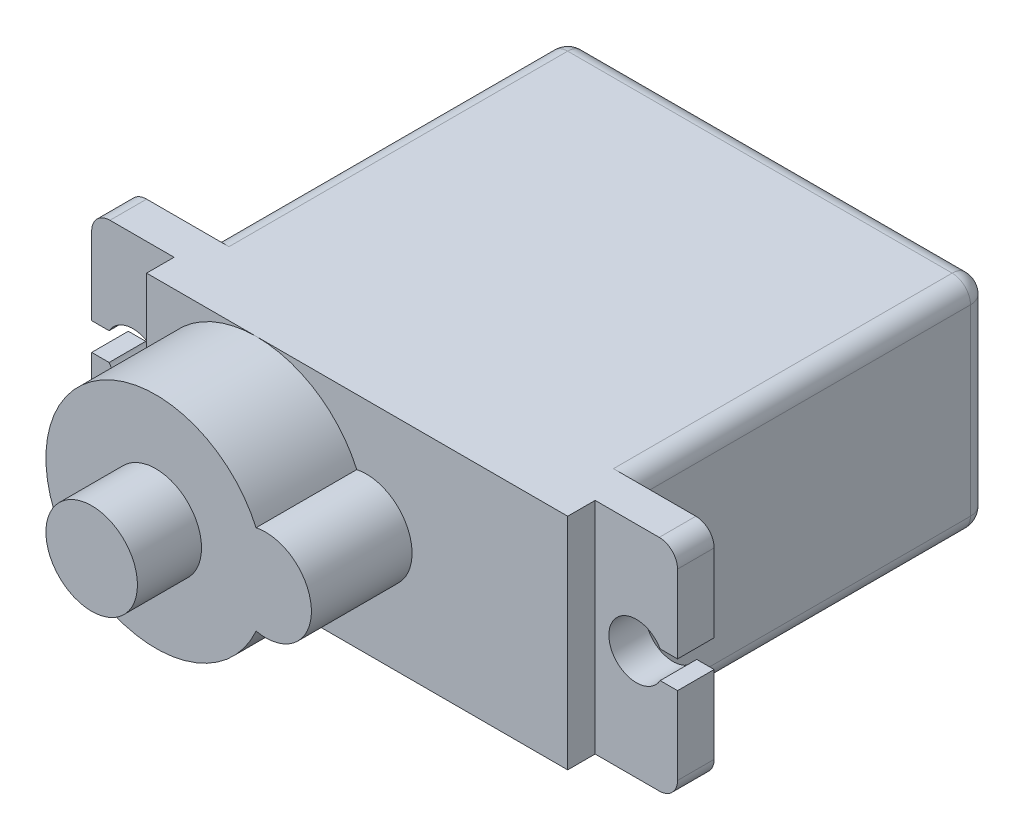
SolidWorks part; units mm, degrees
ref_plane "Front Plane" through (0, 0, 0) normal (0, 0, 1) x (1, 0, 0)
ref_plane "Top Plane" through (0, 0, 0) normal (0, 1, 0) x (1, 0, 0)
ref_plane "Right Plane" through (0, 0, 0) normal (1, 0, 0) x (0, 0, -1)
sketch "Sketch1" plane through (0, 0, 0) normal (0, 0, 1) x (1, 0, 0)
  line L1 (0, 12) -> (23, 12)
  line L2 (0, 12) -> (0, 0)
  line L3 (0, 0) -> (23, 0)
  line L4 (23, 12) -> (23, 0)
  dimension "D1" = 23
  dimension "D2" = 12
extrude "Boss-Extrude1" add sketch "Sketch1" along normal blind 32
sketch "Sketch2" plane through (0, 0, 0) normal (0, -1, 0) x (1, 0, 0)
  line L0 (0, 32) -> (0, 0) construction
  line L1 (-4.5, 21.5) -> (0, 21.5)
  line L2 (-4.5, 21.5) -> (-4.5, 19.5)
  line L3 (-4.5, 19.5) -> (0, 19.5)
  line L4 (0, 21.5) -> (0, 19.5)
  line L5 (23, 32) -> (23, 0) construction
  line L6 (23, 21.5) -> (27.5, 21.5)
  line L7 (23, 21.5) -> (23, 19.5)
  line L8 (23, 19.5) -> (27.5, 19.5)
  line L9 (27.5, 21.5) -> (27.5, 19.5)
  dimension "D1" = 4.5
  dimension "D2" = 2
  dimension "D3" = 19.5
extrude "Boss-Extrude2" add sketch "Sketch2" against normal up to surface (12 mm away) up to face at (11.5, 12, 16)
sketch "Sketch3" plane through (0, 0, 21.5) normal (0, 0, 1) x (1, 0, 0)
  line L0 (-3.549, 6.75) -> (-4.5, 6.75)
  line L1 (-3.549, 5.25) -> (-4.5, 5.25)
  line L2 (26.549, 6.75) -> (27.5, 6.75)
  line L3 (26.549, 5.25) -> (27.5, 5.25)
  line L4 (27.5, 12) -> (27.5, 0) construction
  line L5 (27.5, 6.75) -> (27.5, 5.25)
  line L6 (-4.5, 12) -> (-4.5, 0) construction
  line L7 (-4.5, 6.75) -> (-4.5, 5.25)
  arc A0 (-3.549, 5.25) -> (-3.549, 6.75) centre (-2.25, 6) ccw
  arc A1 (26.549, 6.75) -> (26.549, 5.25) centre (25.25, 6) ccw
  dimension "D4" = 3
  dimension "D1" = 6
  dimension "D2" = 2.25
  dimension "D3" = 2.25
  dimension "D5" = 0.75
  dimension "D6" = 0.75
  dimension "D7" = 0.75
  dimension "D8" = 0.75
extrude "Cut-Extrude1" cut sketch "Sketch3" against normal through all
sketch "Sketch4" plane through (0, 0, 32) normal (0, 0, 1) x (1, 0, 0)
  line L1 (0, 0) -> (23, 0)
  line L2 (0, 0) -> (0, 12)
  line L3 (0, 12) -> (23, 12)
  line L4 (23, 0) -> (23, 12)
  circle A0 centre (6, 6) radius 2.5
  dimension "D3" = 5
  dimension "D1" = 6
  dimension "D2" = 6
extrude "Cut-Extrude2" cut sketch "Sketch4" against normal blind 3.5
sketch "Sketch5" plane through (0, 0, 28.5) normal (0, 0, 1) x (1, 0, 0)
  line L1 (0, 0) -> (23, 0)
  line L2 (0, 0) -> (0, 12)
  line L3 (0, 12) -> (23, 12)
  line L4 (23, 0) -> (23, 12)
  arc A0 (11.4792, 8.4451) -> (11.4792, 3.5549) centre (6, 6) ccw
  arc A1 (11.4792, 3.5549) -> (11.4792, 8.4451) centre (12, 6) ccw
  line M4 (0, 12) -> (0, 0)
  line M5 (0, 0) -> (23, 0)
  line M6 (23, 0) -> (23, 12)
  line M7 (23, 12) -> (0, 12)
  dimension "D1" = 5
  dimension "D2" = 6
extrude "Cut-Extrude3" cut sketch "Sketch5" against normal blind 5.5 contours A1 A0 L1 M6 M7 | A0 L3 M4 | A0 L2 M5
fillet "Fillet1" radius 1 12 edges at (23, 6, 0) (11.5, 12, 0) (0, 6, 0) (11.5, 0, 0) (27.5, 0, 20.5) (27.5, 12, 20.5) (-4.5, 12, 20.5) (-4.5, 0, 20.5)
